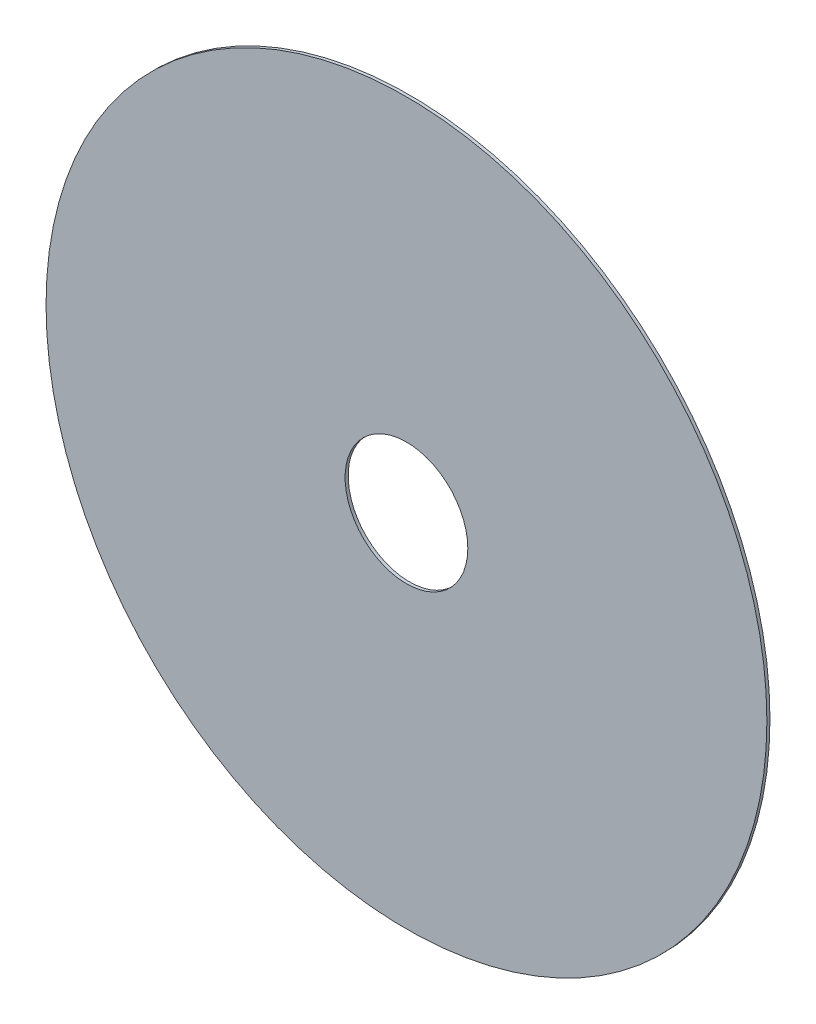
SolidWorks part; units mm, degrees
material "Commercially Pure CP-Ti UNS R50400 (SS)"
ref_plane "Front Plane" through (0, 0, 0) normal (0, 0, 1) x (1, 0, 0)
ref_plane "Top Plane" through (0, 0, 0) normal (0, 1, 0) x (1, 0, 0)
ref_plane "Right Plane" through (0, 0, 0) normal (1, 0, 0) x (0, 0, -1)
sketch "Sketch1" plane through (0, 0, 0) normal (0, 0, 1) x (1, 0, 0)
  circle A0 centre (0, 0) radius 29.845
  dimension "D1" = 59.69
extrude "Boss-Extrude1" add sketch "Sketch1" along normal blind 0.254
hole_wizard "#97 (0.4) Diameter Hole1" positions "Sketch3" profile "Sketch4" hole size "#97" standard "ANSI Inch" end condition through all
sketch "Sketch3" plane through (0, 0, 0.254) normal (0, 0, 1) x (1, 0, 0)
  point P0 (0, 0)
sketch "Sketch4" plane through (0, 0, 0.254) normal (1, 0, 0) x (0, -1, 0)
  line L0 (0, 0) -> (0, 0.254)
  line L1 (0, 0.254) -> (5.08, 0.254)
  line L2 (5.08, 0.254) -> (5.08, 0)
  line L5 (5.08, 0) -> (0, 0)
  line L11 (0, -6.35) -> (0, 107.95) construction
  dimension "Thru Hole Dia." = 10.16
  dimension "Thru Hole Depth" = 0.254
